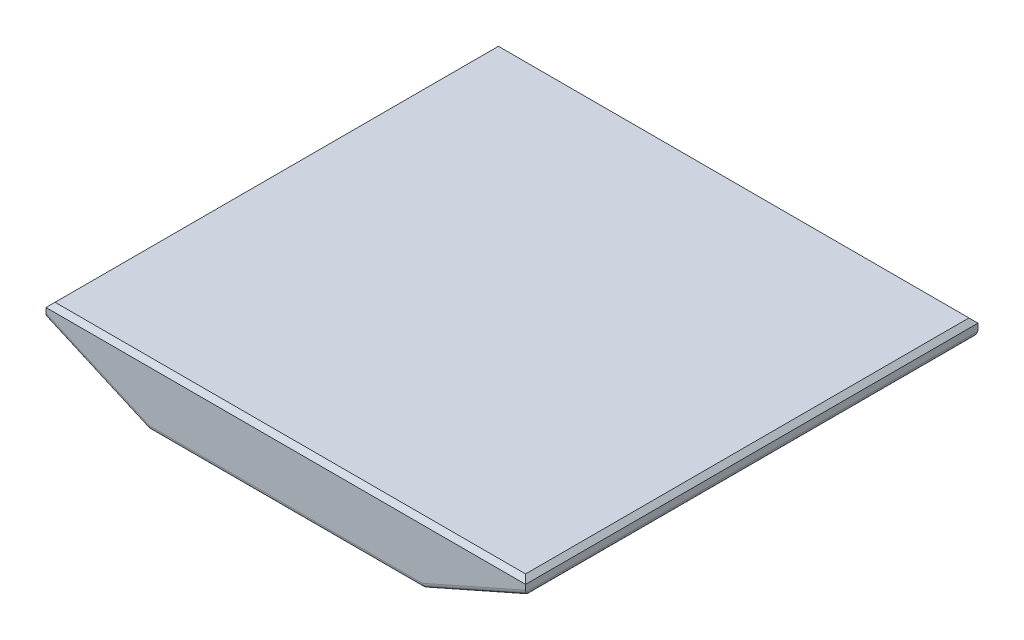
SolidWorks part; units mm, degrees
ref_plane "Спереди" through (0, 0, 0) normal (0, 0, 1) x (1, 0, 0)
ref_plane "Сверху" through (0, 0, 0) normal (0, 1, 0) x (1, 0, 0)
ref_plane "Справа" through (0, 0, 0) normal (1, 0, 0) x (0, 0, -1)
sketch "Эскиз1" plane through (0, 0, 0) normal (0, 0, 1) x (1, 0, 0)
  line L0 (-26.5, 0) -> (26.5, 0)
  line L1 (26.5, 0) -> (26.5, -1.6)
  line L2 (26.5, -1.6) -> (15.2, -6.6)
  line L3 (15.2, -6.6) -> (-15.2, -6.6)
  line L4 (0, 17.4622) -> (0, -34.833) construction
  line L5 (-26.5, -1.6) -> (-15.2, -6.6)
  line L6 (-26.5, 0) -> (-26.5, -1.6)
  point P7 (0, -6.6)
  point P11 (0, 0)
  dimension "D1" = 53
  dimension "D2" = 1.6
  dimension "D3" = 6.6
  dimension "D4" = 30.4
extrude "Бобышка-Вытянуть1" add sketch "Эскиз1" along normal blind 50
chamfer "Фаска1" distance 0.5 angle 45 4 edges at (26.5, 0, 25) (0, 0, 50) (-26.5, 0, 25) (0, 0, 0)
fillet "Скругление1" radius 0.5 10 edges at (20.85, -4.1, 50) (26.5, -1.6, 25) (20.85, -4.1, 0) (0, -6.6, 50) (15.2, -6.6, 25) (0, -6.6, 0) (-26.5, -1.6, 25) (-20.85, -4.1, 50) (-15.2, -6.6, 25) (-20.85, -4.1, 0)
